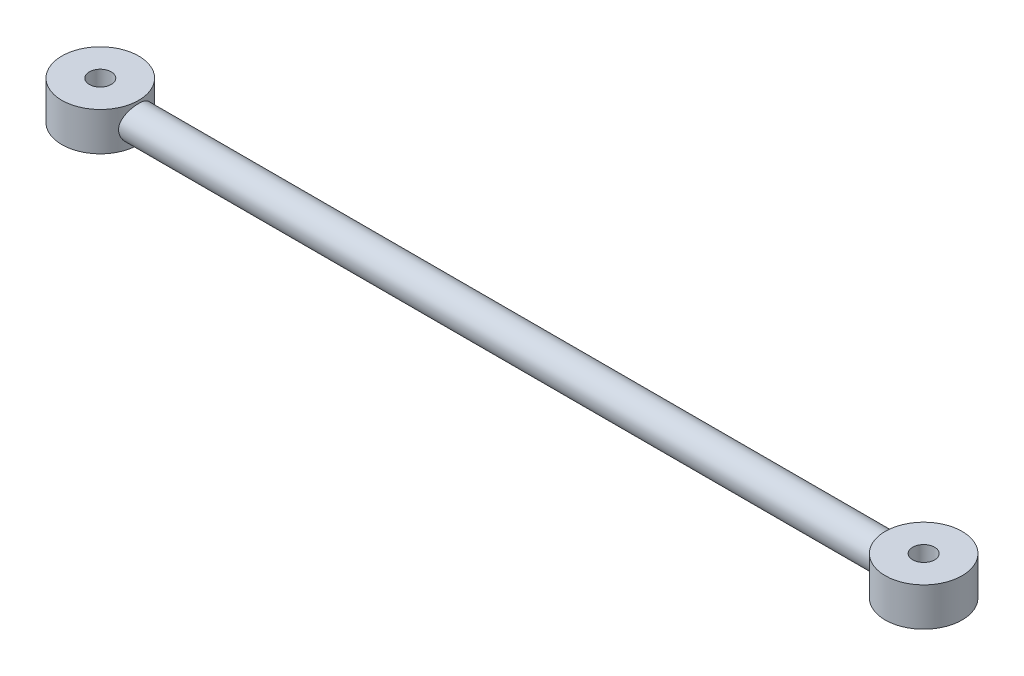
SolidWorks part; units mm, degrees
ref_plane "Front Plane" through (0, 0, 0) normal (0, 0, 1) x (1, 0, 0)
ref_plane "Top Plane" through (0, 0, 0) normal (0, 1, 0) x (1, 0, 0)
ref_plane "Right Plane" through (0, 0, 0) normal (1, 0, 0) x (0, 0, -1)
sketch "Sketch1" plane through (0, 0, 0) normal (0, 1, 0) x (1, 0, 0)
  line L0 (0, 0) -> (150, 0) construction
  circle A0 centre (0, 0) radius 7
  circle A1 centre (150, 0) radius 7
  circle A2 centre (0, 0) radius 2
  circle A3 centre (150, 0) radius 2
  dimension "D2" = 4
  dimension "D5" = 14
  dimension "D1" = 150
extrude "Boss-Extrude1" add sketch "Sketch1" along normal blind 7
ref_plane "Plane1" through (150, 0, 0) normal (1, 0, 0) x (0, 0, -1)
ref_plane "Plane2" through (22.5, 0, 0) normal (1, 0, 0) x (0, 0, -1)
sketch "Sketch2" plane through (22.5, 0, 0) normal (1, 0, 0) x (0, 0, -1)
  line L0 (0, 0) -> (0, 3.5) construction
  circle A0 centre (0, 3.5) radius 3
  dimension "D2" = 6
  dimension "D1" = 3.5
extrude "Boss-Extrude2" add sketch "Sketch2" along normal up to surface and the other way up to surface up to face at (150, 7, 7) other way up to face at (0, 7, 7)
